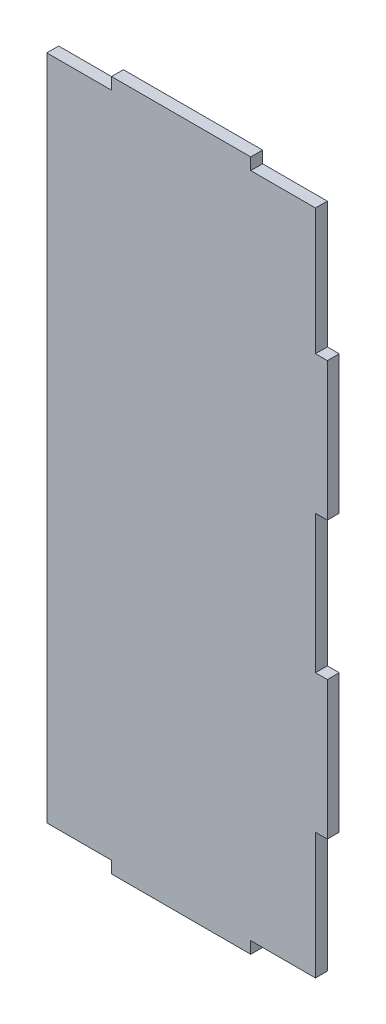
SolidWorks part; units mm, degrees
ref_plane "Alzado" through (0, 0, 0) normal (0, 0, 1) x (1, 0, 0)
ref_plane "Planta" through (0, 0, 0) normal (0, 1, 0) x (1, 0, 0)
ref_plane "Vista lateral" through (0, 0, 0) normal (1, 0, 0) x (0, 0, -1)
sketch "Croquis1" plane through (0, 0, 0) normal (0, 0, 1) x (1, 0, 0)
  line L0 (45.427, 366.8208) -> (75.427, 366.8208)
  line L1 (-49.073, 366.8208) -> (-19.073, 366.8208)
  line L2 (-19.073, 57.8208) -> (-19.073, 52.3208)
  line L3 (45.427, 57.8208) -> (75.427, 57.8208)
  line L4 (75.427, 57.8208) -> (75.427, 116.3208)
  line L5 (-19.073, 366.8208) -> (-19.073, 372.3208)
  line L6 (75.427, 366.8208) -> (75.427, 308.3208)
  line L7 (45.427, 366.8208) -> (45.427, 372.3208)
  line L8 (-19.073, 52.3208) -> (45.427, 52.3208)
  line L9 (45.427, 52.3208) -> (45.427, 57.8208)
  line L10 (75.427, 116.3208) -> (80.927, 116.3208)
  line L11 (80.927, 308.3208) -> (80.927, 244.3208) construction
  line L12 (80.927, 180.3208) -> (80.927, 116.3208) construction
  line L13 (80.927, 116.3208) -> (80.927, 180.3208)
  line L14 (75.427, 180.3208) -> (80.927, 180.3208)
  line L15 (75.427, 180.3208) -> (75.427, 244.3208)
  line L16 (80.927, 244.3208) -> (75.427, 244.3208)
  line L17 (80.927, 244.3208) -> (80.927, 308.3208)
  line L18 (75.427, 308.3208) -> (80.927, 308.3208)
  line L19 (-19.073, 366.8208) -> (45.427, 366.8208) construction
  line L20 (45.427, 372.3208) -> (-19.073, 372.3208)
  line L21 (-19.073, 57.8208) -> (-49.073, 57.8208)
  line L22 (-49.073, 57.8208) -> (-49.073, 366.8208)
  line L23 (-19.073, 57.8208) -> (45.427, 57.8208) construction
  line L24 (-19.073, 366.8208) -> (-19.073, 57.8208) construction
  line L25 (45.427, 57.8208) -> (45.427, 366.8208) construction
  line L26 (75.427, 308.3208) -> (75.427, 366.8208) construction
  line L27 (75.427, 244.3208) -> (75.427, 180.3208) construction
  line L28 (75.427, 116.3208) -> (75.427, 57.8208) construction
  dimension "D1" = 320
  dimension "D3" = 30
  dimension "D4" = 30
  dimension "D5" = 5.5
extrude "Saliente-Extruir1" add sketch "Croquis1" along normal blind 5.5
